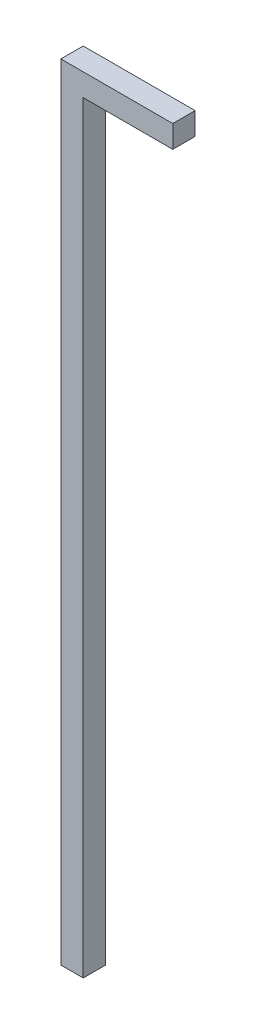
SolidWorks part; units mm, degrees
ref_plane "Front Plane" through (0, 0, 0) normal (0, 0, 1) x (1, 0, 0)
ref_plane "Top Plane" through (0, 0, 0) normal (0, 1, 0) x (1, 0, 0)
ref_plane "Right Plane" through (0, 0, 0) normal (1, 0, 0) x (0, 0, -1)
sketch "Sketch1" plane through (0, 0, 0) normal (0, 0, 1) x (1, 0, 0)
  line L0 (-183.9741, 211.5464) -> (-283.9741, 211.5464)
  line L1 (-283.9741, 211.5464) -> (-283.9741, -489.7836)
  line L2 (-283.9741, -489.7836) -> (-263.9741, -489.7836)
  line L3 (-263.9741, -489.7836) -> (-263.9741, 191.5464)
  line L4 (-263.9741, 191.5464) -> (-183.9741, 191.5464)
  line L5 (-183.9741, 211.5464) -> (-183.9741, 191.5464)
  dimension "D1" = 701.33
  dimension "D2" = 100
  dimension "D3" = 20
  dimension "D4" = 20
extrude "Boss-Extrude1" add sketch "Sketch1" along normal blind 20
